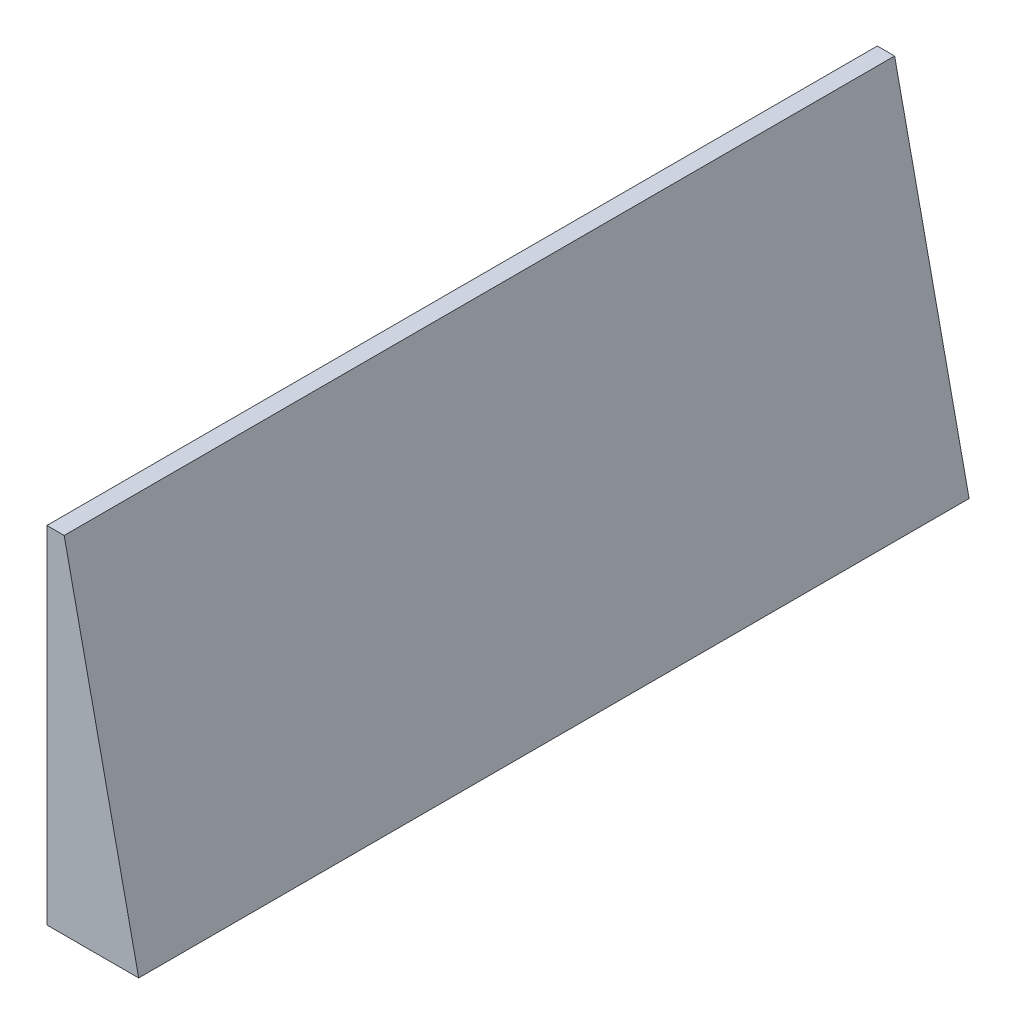
SolidWorks part; units mm, degrees
ref_plane "Front" through (0, 0, 0) normal (0, 0, 1) x (1, 0, 0)
ref_plane "Top" through (0, 0, 0) normal (0, 1, 0) x (1, 0, 0)
ref_plane "Right" through (0, 0, 0) normal (1, 0, 0) x (0, 0, -1)
sketch "Sketch1" plane through (0, 0, 0) normal (0, 0, 1) x (1, 0, 0)
  line L0 (-1.5875, 31.75) -> (1.5875, 31.75)
  line L1 (1.5875, 31.75) -> (15.2587, -31.75)
  line L2 (15.2587, -31.75) -> (-1.5875, -31.75)
  line L3 (-1.5875, -31.75) -> (-1.5875, 31.75)
  line L4 (15.2587, -31.75) -> (15.2587, -31.2802) construction
  line L5 (50, 0) -> (-50, 0) construction
  line L6 (0, -50) -> (0, 50) construction
  point P5 (-1.5875, 0)
  point P9 (0, 31.75)
  dimension "D1" = 3.175
  dimension "D2" = 63.5
  dimension "D3" = 12.15
extrude "Boss-Extrude1" add sketch "Sketch1" along normal mid plane 152.4
